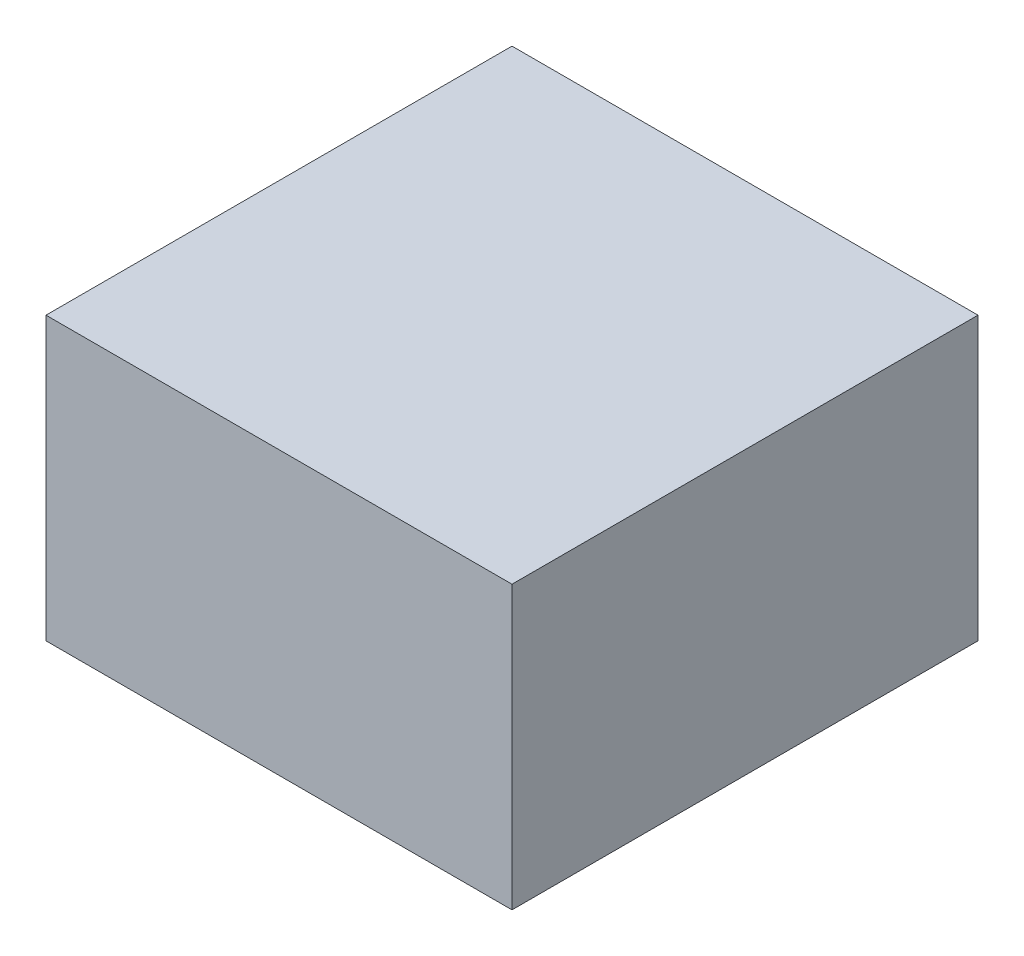
SolidWorks part; units mm, degrees
ref_plane "Front Plane" through (0, 0, 0) normal (0, 0, 1) x (1, 0, 0)
ref_plane "Top Plane" through (0, 0, 0) normal (0, 1, 0) x (1, 0, 0)
ref_plane "Right Plane" through (0, 0, 0) normal (1, 0, 0) x (0, 0, -1)
sketch "Sketch1" plane through (0, 0, 0) normal (0, 1, 0) x (1, 0, 0)
  line L1 (-19, -19) -> (19, -19)
  line L2 (-19, -19) -> (-19, 19)
  line L3 (-19, 19) -> (19, 19)
  line L4 (19, -19) -> (19, 19)
  line L5 (-19, -19) -> (19, 19) construction
  line L6 (-19, 19) -> (19, -19) construction
  point P0 (0, 0)
  dimension "D1" = 38
  dimension "D2" = 38
extrude "Boss-Extrude1" add sketch "Sketch1" along normal blind 23 contours L2 L1 L4 L3
